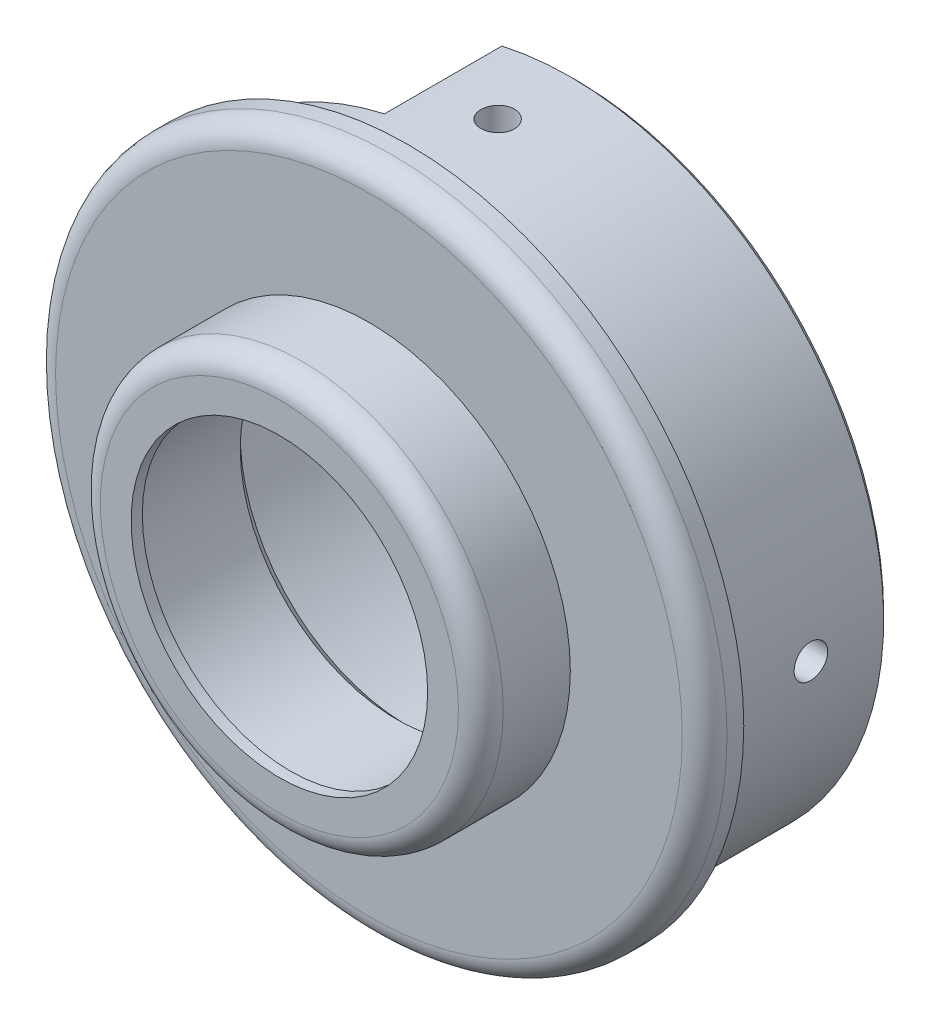
SolidWorks part; units mm, degrees
ref_plane "정면" through (0, 0, 0) normal (0, 0, 1) x (1, 0, 0)
ref_plane "윗면" through (0, 0, 0) normal (0, 1, 0) x (1, 0, 0)
ref_plane "우측면" through (0, 0, 0) normal (1, 0, 0) x (0, 0, -1)
sketch "스케치2" plane through (0, 0, 0) normal (0, 0, 1) x (1, 0, 0)
  circle A0 centre (0, 0) radius 30
  circle A1 centre (0, 0) radius 14
extrude "보스-돌출1" add sketch "스케치2" along normal blind 11.5
sketch "스케치3" plane through (0, 0, 11.5) normal (0, 0, 1) x (1, 0, 0)
  circle A0 centre (0, 0) radius 14
  circle A1 centre (0, 0) radius 13.25
extrude "보스-돌출2" add sketch "스케치3" against normal blind 1.5
sketch "스케치4" plane through (0, 0, 11.5) normal (0, 0, 1) x (1, 0, 0)
  circle A1 centre (0, 0) radius 18
  circle A2 centre (0, 0) radius 33.7606
extrude "컷-돌출1" cut sketch "스케치4" against normal blind 8
fillet "필렛1" radius 2 1 edges at (18, 0, 11.5)
fillet "필렛2" radius 2 1 edges at (30, 0, 3.5)
sketch "스케치5" plane through (0, 0, 0) normal (0, 0, -1) x (-1, 0, 0)
sketch "스케치6" plane through (0, 0, 0) normal (0, 0, -1) x (-1, 0, 0)
  circle A0 centre (0, 0) radius 28
  circle A1 centre (0, 0) radius 23
extrude "보스-돌출3" add sketch "스케치6" along normal blind 15
sketch "스케치7" plane through (0, 0, 0) normal (0, 1, 0) x (1, 0, 0)
  line L0 (0, -14.575) -> (0, 14.575) construction
  line L1 (-33, 0) -> (33, 0) construction
  circle A0 centre (0, 8) radius 1.5
  dimension "D1" = 8
extrude "컷-돌출2" cut sketch "스케치7" against normal through all and the other way through all
sketch "스케치8" plane through (0, 0, 0) normal (1, 0, 0) x (0, 0, -1)
  line L0 (14.575, 0) -> (-14.575, 0) construction
  line L1 (0, 33) -> (0, -33) construction
  circle A0 centre (8, 0) radius 1.5
  dimension "D1" = 8
extrude "컷-돌출3" cut sketch "스케치8" against normal through all and the other way through all
sketch "스케치13" plane through (0, 0, -15) normal (0, 0, -1) x (-1, 0, 0)
  line L0 (0, 0) -> (9.1924, 9.1924) construction
  line L1 (14.575, 0) -> (-14.575, 0) construction
  line L3 (19.799, 19.799) -> (30.4056, 9.1924)
  line L4 (9.1924, 9.1924) -> (19.799, -1.4142)
  line L5 (30.4056, 9.1924) -> (19.799, -1.4142)
  line L7 (19.799, 19.799) -> (9.1924, 30.4056)
  line L8 (9.1924, 9.1924) -> (-1.4142, 19.799)
  line L9 (9.1924, 30.4056) -> (-1.4142, 19.799)
  line L10 (19.799, 19.799) -> (27.234, 27.234) construction
  circle A0 centre (0, 0) radius 28 construction
  dimension "D1" = 45
  dimension "D2" = 15
  dimension "D3" = 15
  dimension "D4" = 15
extrude "컷-돌출4" cut sketch "스케치13" against normal blind 11
sketch "스케치15" plane through (0, 0, 10) normal (0, 0, -1) x (-1, 0, 0)
  circle A0 centre (0, 0) radius 14
extrude "컷-돌출5" cut sketch "스케치15" against normal blind 0.5
chamfer "모따기1" distance 1 angle 45 1 edges at (14, 0, 0)
chamfer "모따기2" distance 0.5 angle 45 1 edges at (19.799, -19.799, -15)
